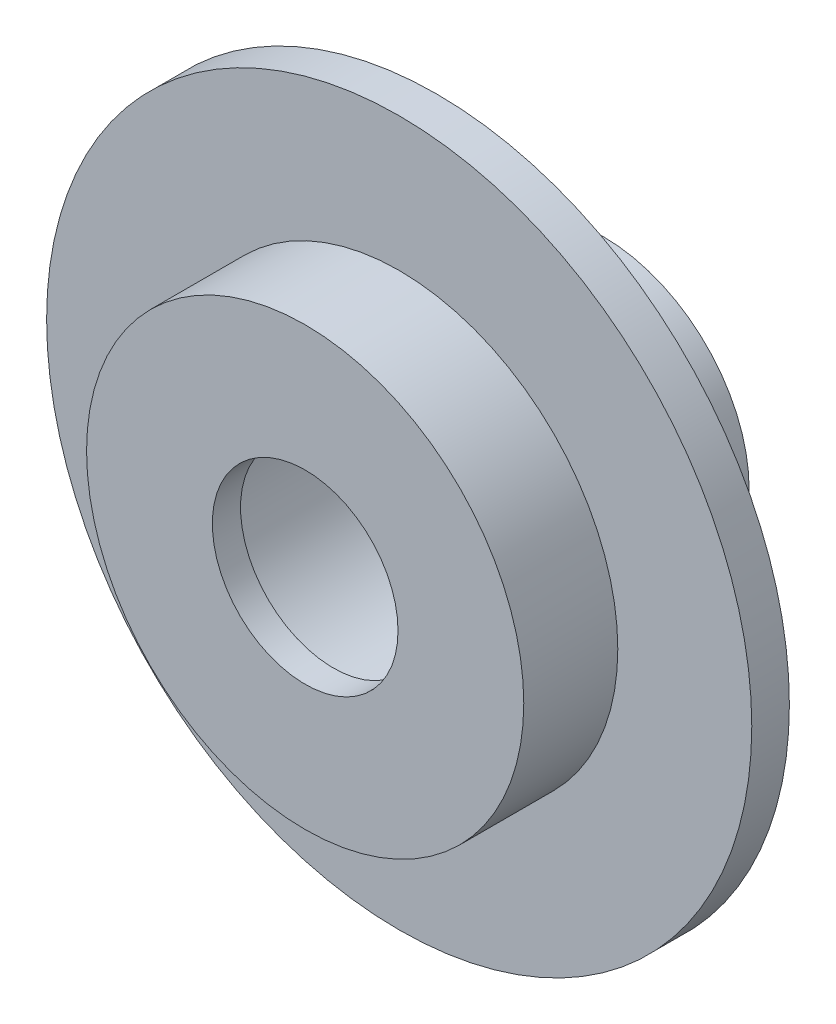
SolidWorks part; units mm, degrees
ref_plane "Plan de face" through (0, 0, 0) normal (0, 0, 1) x (1, 0, 0)
ref_plane "Plan de dessus" through (0, 0, 0) normal (0, 1, 0) x (1, 0, 0)
ref_plane "Plan de droite" through (0, 0, 0) normal (1, 0, 0) x (0, 0, -1)
sketch "Esquisse1" plane through (0, 0, 0) normal (0, 0, 1) x (1, 0, 0)
  circle A0 centre (0, 0) radius 19.05
  dimension "D1" = 38.1
extrude "Boss.-Extru.1" add sketch "Esquisse1" along normal blind 2.032
sketch "Esquisse2" plane through (0, 0, 2.032) normal (0, 0, 1) x (1, 0, 0)
  circle A0 centre (0, 0) radius 11.811
  dimension "D1" = 23.622
extrude "Boss.-Extru.2" add sketch "Esquisse2" along normal blind 5.08
sketch "Esquisse3" plane through (0, 0, 7.112) normal (0, 0, 1) x (1, 0, 0)
  circle A1 centre (0, 0) radius 5.0165
  point P2 (-4.6054, 11.5273)
  dimension "D1" = 10.033
extrude "Enlèv. mat.-Extru.1" cut sketch "Esquisse3" against normal blind 1.524
sketch "Esquisse4" plane through (0, 0, 0) normal (0, 0, -1) x (-1, 0, 0)
  circle A0 centre (0, 0) radius 7.875
  dimension "D1" = 15.75
extrude "Boss.-Extru.3" add sketch "Esquisse4" along normal blind 9
sketch "Esquisse5" plane through (0, 0, -9) normal (0, 0, -1) x (-1, 0, 0)
  circle A0 centre (0, 0) radius 6.875
  circle A1 centre (0, 0) radius 7.875 construction
  dimension "D1" = 1
extrude "Enlèv. mat.-Extru.2" cut sketch "Esquisse5" against normal up to surface (14.588 mm away) up to face at (5.0165, 0, 5.588)
